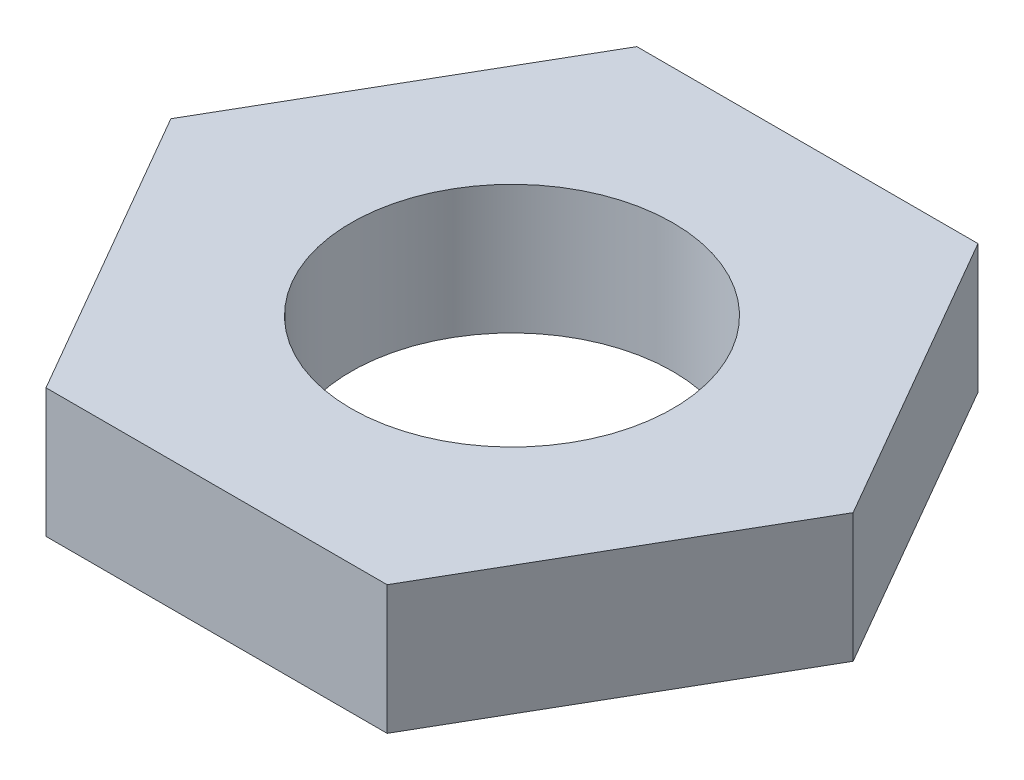
SolidWorks part; units mm, degrees
ref_plane "前视基准面" through (0, 0, 0) normal (0, 0, 1) x (1, 0, 0)
ref_plane "上视基准面" through (0, 0, 0) normal (0, 1, 0) x (1, 0, 0)
ref_plane "右视基准面" through (0, 0, 0) normal (1, 0, 0) x (0, 0, -1)
sketch "草图4" plane through (0, 0, 0) normal (0, 1, 0) x (1, 0, 0)
  line L0 (-12.7945, 0) -> (16.3015, 0) construction
  line L2 (1.325, -2.295) -> (2.65, 0)
  line L3 (2.65, 0) -> (1.325, 2.295)
  line L4 (1.325, 2.295) -> (-1.325, 2.295)
  line L5 (-1.325, 2.295) -> (-2.65, 0)
  line L6 (-2.65, 0) -> (-1.325, -2.295)
  line L7 (-1.325, -2.295) -> (1.325, -2.295)
  circle A0 centre (0, 0) radius 2.295 construction
  dimension "D1" = 5.3
extrude "凸台-拉伸1" add sketch "草图4" along normal blind 1
sketch "草图6" plane through (0, 0, 0) normal (0, -1, 0) x (-1, 0, 0)
  circle A0 centre (0, 0) radius 1.6
  dimension "D1" = 3.2
sketch "草图7" plane through (0, 1, 0) normal (0, 1, 0) x (1, 0, 0)
  circle A0 centre (0, 0) radius 1.25
  dimension "D1" = 2.5
extrude "切除-拉伸1" cut sketch "草图7" against normal blind 5
cosmetic thread "装饰螺纹线2" parameters "D2"=3
